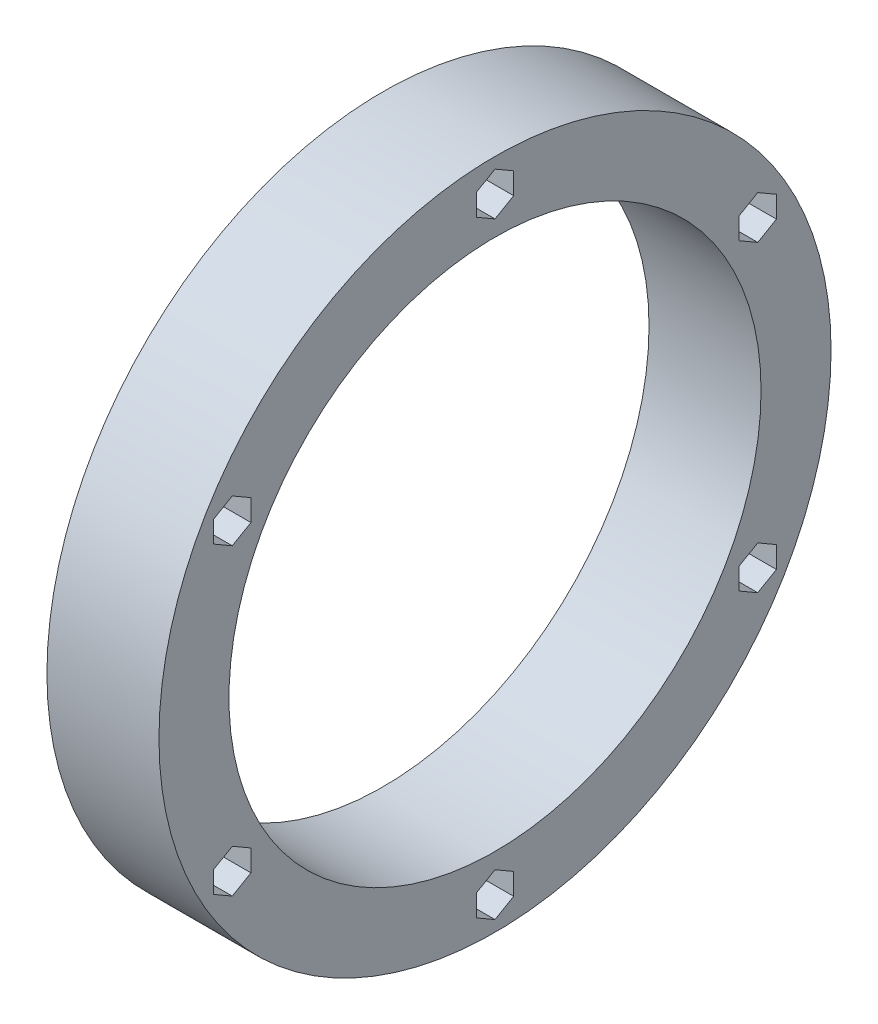
SolidWorks part; units mm, degrees
ref_plane "Front Plane" through (0, 0, 0) normal (0, 0, 1) x (1, 0, 0)
ref_plane "Top Plane" through (0, 0, 0) normal (0, 1, 0) x (1, 0, 0)
ref_plane "Right Plane" through (0, 0, 0) normal (1, 0, 0) x (0, 0, -1)
sketch "Sketch1" plane through (0, 0, 0) normal (1, 0, 0) x (0, 0, -1)
  circle A0 centre (0, 0) radius 72
  circle A1 centre (0, 0) radius 57
  dimension "D1" = 144
  dimension "D2" = 15
extrude "Boss-Extrude1" add sketch "Sketch1" along normal blind 24
sketch "Sketch2" plane through (24, 0, 0) normal (1, 0, 0) x (0, 0, -1)
  line L0 (52.2917, 30.1906) -> (56.2917, 27.8812)
  line L1 (0, 60.3812) -> (4, 62.6906)
  line L2 (4, 62.6906) -> (4, 67.3094)
  line L3 (4, 67.3094) -> (0, 69.6188)
  line L4 (0, 69.6188) -> (-4, 67.3094)
  line L5 (-4, 67.3094) -> (-4, 62.6906)
  line L6 (-4, 62.6906) -> (0, 60.3812)
  line L7 (56.2917, 27.8812) -> (60.2917, 30.1906)
  line L8 (60.2917, 30.1906) -> (60.2917, 34.8094)
  line L9 (60.2917, 34.8094) -> (56.2917, 37.1188)
  line L10 (56.2917, 37.1188) -> (52.2917, 34.8094)
  line L11 (52.2917, 34.8094) -> (52.2917, 30.1906)
  line L12 (52.2917, -30.1906) -> (52.2917, -34.8094)
  line L13 (52.2917, -34.8094) -> (56.2917, -37.1188)
  line L14 (56.2917, -37.1188) -> (60.2917, -34.8094)
  line L15 (60.2917, -34.8094) -> (60.2917, -30.1906)
  line L16 (60.2917, -30.1906) -> (56.2917, -27.8812)
  line L17 (56.2917, -27.8812) -> (52.2917, -30.1906)
  line L18 (0, -60.3812) -> (-4, -62.6906)
  line L19 (-4, -62.6906) -> (-4, -67.3094)
  line L20 (-4, -67.3094) -> (0, -69.6188)
  line L21 (0, -69.6188) -> (4, -67.3094)
  line L22 (4, -67.3094) -> (4, -62.6906)
  line L23 (4, -62.6906) -> (0, -60.3812)
  line L24 (-52.2917, -30.1906) -> (-56.2917, -27.8812)
  line L25 (-56.2917, -27.8812) -> (-60.2917, -30.1906)
  line L26 (-60.2917, -30.1906) -> (-60.2917, -34.8094)
  line L27 (-60.2917, -34.8094) -> (-56.2917, -37.1188)
  line L28 (-56.2917, -37.1188) -> (-52.2917, -34.8094)
  line L29 (-52.2917, -34.8094) -> (-52.2917, -30.1906)
  line L30 (-52.2917, 30.1906) -> (-52.2917, 34.8094)
  line L31 (-52.2917, 34.8094) -> (-56.2917, 37.1188)
  line L32 (-56.2917, 37.1188) -> (-60.2917, 34.8094)
  line L33 (-60.2917, 34.8094) -> (-60.2917, 30.1906)
  line L34 (-60.2917, 30.1906) -> (-56.2917, 27.8812)
  line L35 (-56.2917, 27.8812) -> (-52.2917, 30.1906)
  circle A0 centre (0, 65) radius 4 construction
  circle A1 centre (56.2917, 32.5) radius 4 construction
  circle A2 centre (56.2917, -32.5) radius 4 construction
  circle A3 centre (0, -65) radius 4 construction
  circle A4 centre (-56.2917, -32.5) radius 4 construction
  circle A5 centre (-56.2917, 32.5) radius 4 construction
  point P52 (0, 0)
  dimension "D1" = 8
  dimension "D2" = 65
  dimension "D3" = 6
extrude "Cut-Extrude1" cut sketch "Sketch2" against normal blind 24
